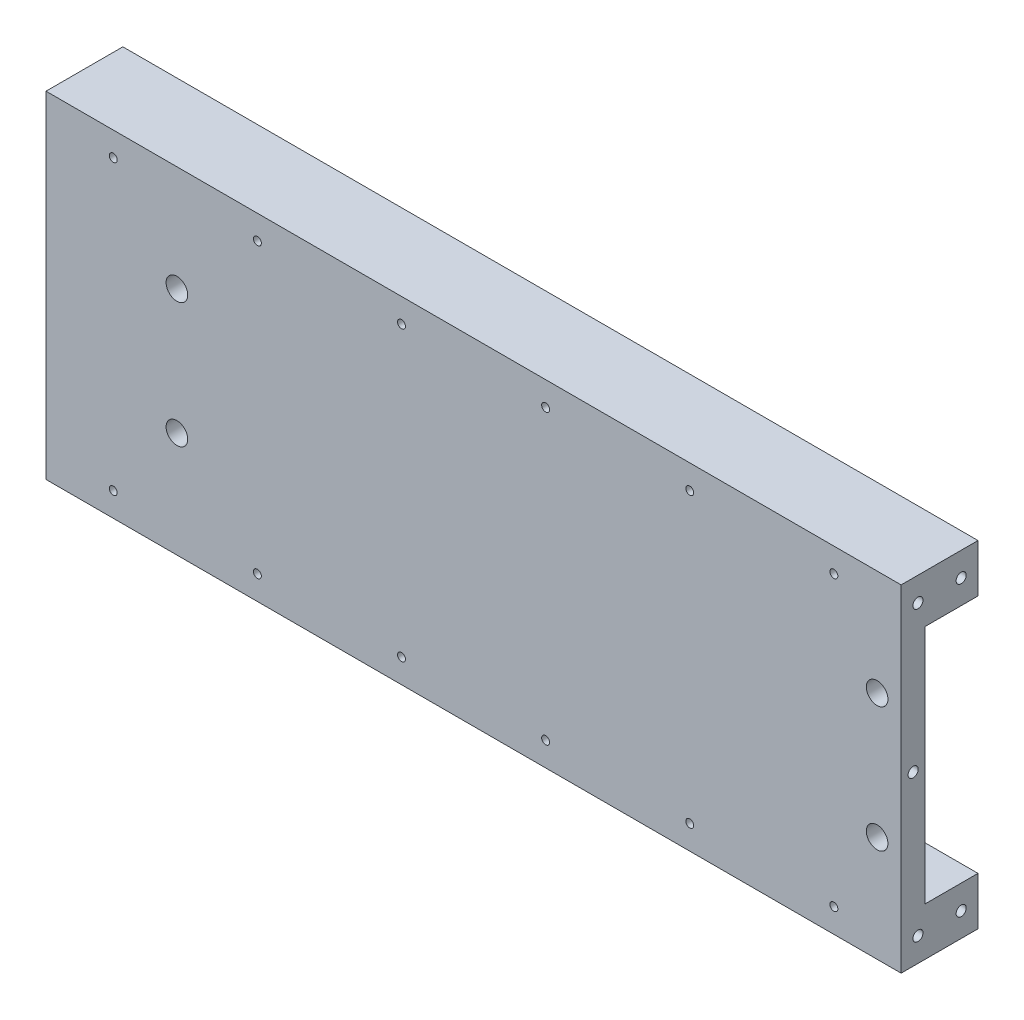
SolidWorks part; units mm, degrees
ref_plane "前视基准面" through (0, 0, 0) normal (0, 0, 1) x (1, 0, 0)
ref_plane "上视基准面" through (0, 0, 0) normal (0, 1, 0) x (1, 0, 0)
ref_plane "右视基准面" through (0, 0, 0) normal (1, 0, 0) x (0, 0, -1)
other "Configuration Table"
sketch "草图1" plane through (0, 0, 0) normal (1, 0, 0) x (0, 0, -1)
  line L0 (0, 0) -> (32, 0)
  line L1 (32, 0) -> (32, -20)
  line L2 (32, -20) -> (10, -20)
  line L3 (10, -20) -> (10, -120)
  line L4 (10, -120) -> (32, -120)
  line L5 (32, -120) -> (32, -140)
  line L6 (32, -140) -> (0, -140)
  line L7 (0, -140) -> (0, 0)
  dimension "D1" = 20
  dimension "D2" = 20
  dimension "D3" = 10
  dimension "D4" = 100
  dimension "D5" = 32
  dimension "D6" = 32
extrude "凸台-拉伸1" add sketch "草图1" along normal blind 356
sketch "草图2" plane through (356, 0, 0) normal (1, 0, 0) x (0, 0, -1)
  line L0 (0, -70) -> (12.9314, -70) construction
  line L1 (0, 0) -> (0, -140) construction
  circle A0 centre (25, -130) radius 2.5
  circle A1 centre (7, -130) radius 2.5
  circle A4 centre (7, -10) radius 2.5
  circle A5 centre (25, -10) radius 2.5
  circle A6 centre (5, -70) radius 2.5
  dimension "D1" = 5
  dimension "D2" = 5
hole_wizard "M5 螺纹孔1" positions "3D草图4" profile "草图5" tap size "M5" standard "GB"
sketch3d "3D草图4"
  point P0 (356, -130, -25)
  point P3 (356, -130, -7)
  point P12 (356, -10, -7)
  point P15 (356, -10, -25)
  point P21 (356, -70, -5)
sketch "草图5" plane through (356, -130, -25) normal (0, 1, 0) x (0, 0, -1)
  line L0 (0, 0) -> (0, 13.2618)
  line L1 (0, 13.2618) -> (2.1, 12)
  line L2 (2.1, 12) -> (2.1, 0)
  line L5 (2.1, 0) -> (0, 0)
  line L10 (0, 13.2618) -> (-2.1, 12) construction
  line L11 (0, -6.35) -> (0, 107.95) construction
  dimension "螺纹孔钻头直径" = 4.2
  dimension "螺纹孔钻头深度" = 12
  dimension "导头角度" = 118
cosmetic thread "孔螺蚊线1" parameters "D1"=10, "D2"=5
cosmetic thread "孔螺蚊线2" parameters "D1"=10, "D2"=5
cosmetic thread "孔螺蚊线5" parameters "D1"=10, "D2"=5
cosmetic thread "孔螺蚊线6" parameters "D1"=10, "D2"=5
cosmetic thread "孔螺蚊线13" parameters "D1"=10, "D2"=5
sketch "草图13" plane through (0, 0, -10) normal (0, 0, -1) x (-1, 0, 0)
  circle A0 centre (-346, -44) radius 4.5
  circle A1 centre (-346, -96) radius 4.5
  circle A2 centre (-54.5, -44) radius 4.5
  circle A3 centre (-54.5, -96) radius 4.5
extrude "切除-拉伸1" cut sketch "草图13" against normal through all
sketch "草图15" plane through (0, 0, 0) normal (-1, 0, 0) x (0, 0, 1)
  circle A0 centre (-25, -10) radius 2.5
  circle A1 centre (-7, -10) radius 2.5
  circle A2 centre (-5, -70) radius 2.5
  circle A3 centre (-7, -130) radius 2.5
  circle A4 centre (-25, -130) radius 2.5
sketch "草图17" plane through (0, 0, -32) normal (0, 0, -1) x (-1, 0, 0)
  circle A0 centre (-328, -10) radius 2.25
  circle A1 centre (-328, -130) radius 2.25
  dimension "D1" = 4.5
  dimension "D2" = 4.5
hole_wizard "M4 螺纹孔1" positions "3D草图6" profile "草图18" tap size "M4" standard "GB" end condition through all
sketch3d "3D草图6"
  point P0 (328, -130, -32)
  point P3 (328, -10, -32)
sketch "草图18" plane through (328, -130, -32) normal (1, 0, 0) x (0, 1, 0)
  line L0 (0, 0) -> (0, 32)
  line L1 (0, 32) -> (1.65, 32)
  line L2 (1.65, 32) -> (1.65, 0)
  line L5 (1.65, 0) -> (0, 0)
  line L11 (0, -6.35) -> (0, 107.95) construction
  dimension "通孔螺纹孔钻头直径" = 3.3
  dimension "通孔螺纹孔钻头深度" = 32
cosmetic thread "孔螺蚊线19" parameters "D2"=4
cosmetic thread "孔螺蚊线20" parameters "D2"=4
pattern_linear "阵列(线性)1" count 6 spacing 60 along (-1, 0, 0) of "M4 螺纹孔1"
hole_wizard "M5 螺纹孔2" positions "草图19" profile "草图20" tap size "M5" standard "GB"
sketch "草图19" plane through (0, 0, 0) normal (-1, 0, 0) x (0, 0, 1)
  point P0 (-7, -10)
  point P3 (-25, -10)
  point P6 (-5, -70)
  point P9 (-7, -130)
  point P12 (-25, -130)
sketch "草图20" plane through (0, -10, -7) normal (0, 1, 0) x (0, 0, 1)
  line L0 (0, 0) -> (0, 13.2618)
  line L1 (0, 13.2618) -> (2.1, 12)
  line L2 (2.1, 12) -> (2.1, 0)
  line L5 (2.1, 0) -> (0, 0)
  line L10 (0, 13.2618) -> (-2.1, 12) construction
  line L11 (0, -6.35) -> (0, 107.95) construction
  dimension "螺纹孔钻头直径" = 4.2
  dimension "螺纹孔钻头深度" = 12
  dimension "导头角度" = 118
cosmetic thread "孔螺蚊线21" parameters "D1"=10, "D2"=5
cosmetic thread "孔螺蚊线22" parameters "D1"=10, "D2"=5
cosmetic thread "孔螺蚊线23" parameters "D1"=10, "D2"=5
cosmetic thread "孔螺蚊线24" parameters "D1"=10, "D2"=5
cosmetic thread "孔螺蚊线25" parameters "D1"=10, "D2"=5
